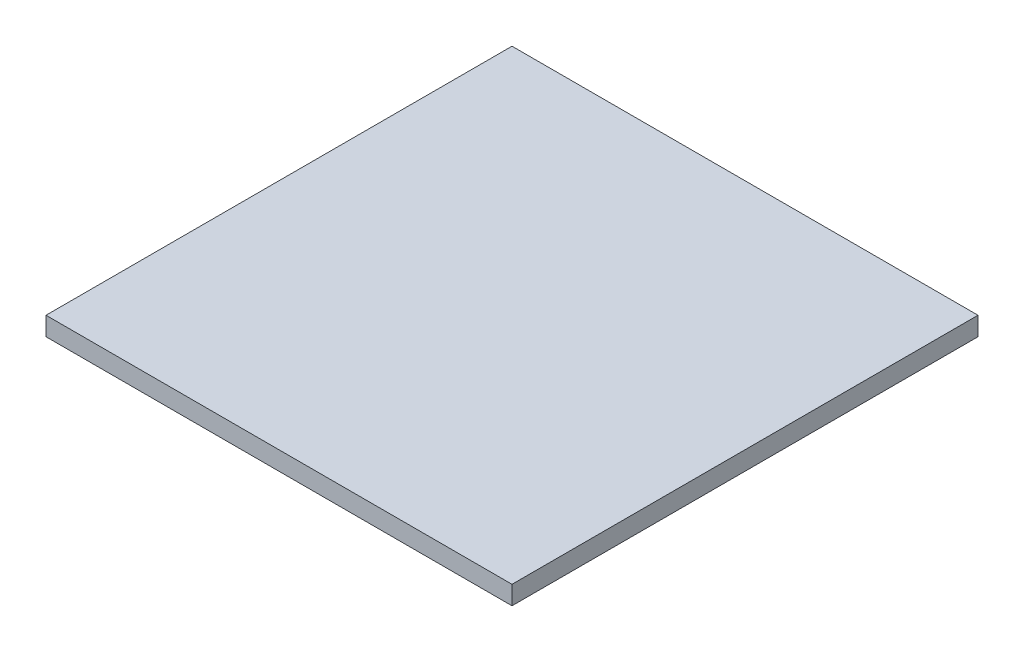
SolidWorks part; units mm, degrees
ref_plane "前视基准面" through (0, 0, 0) normal (0, 0, 1) x (1, 0, 0)
ref_plane "上视基准面" through (0, 0, 0) normal (0, 1, 0) x (1, 0, 0)
ref_plane "右视基准面" through (0, 0, 0) normal (1, 0, 0) x (0, 0, -1)
other "Configuration Table"
sketch "草图1" plane through (0, 0, 0) normal (0, 1, 0) x (1, 0, 0)
  line L1 (0, 0) -> (-200, 0)
  line L2 (0, 0) -> (0, 200)
  line L3 (0, 200) -> (-200, 200)
  line L4 (-200, 0) -> (-200, 200)
  dimension "D1" = 200
  dimension "D2" = 200
extrude "凸台-拉伸1" add sketch "草图1" along normal blind 8
